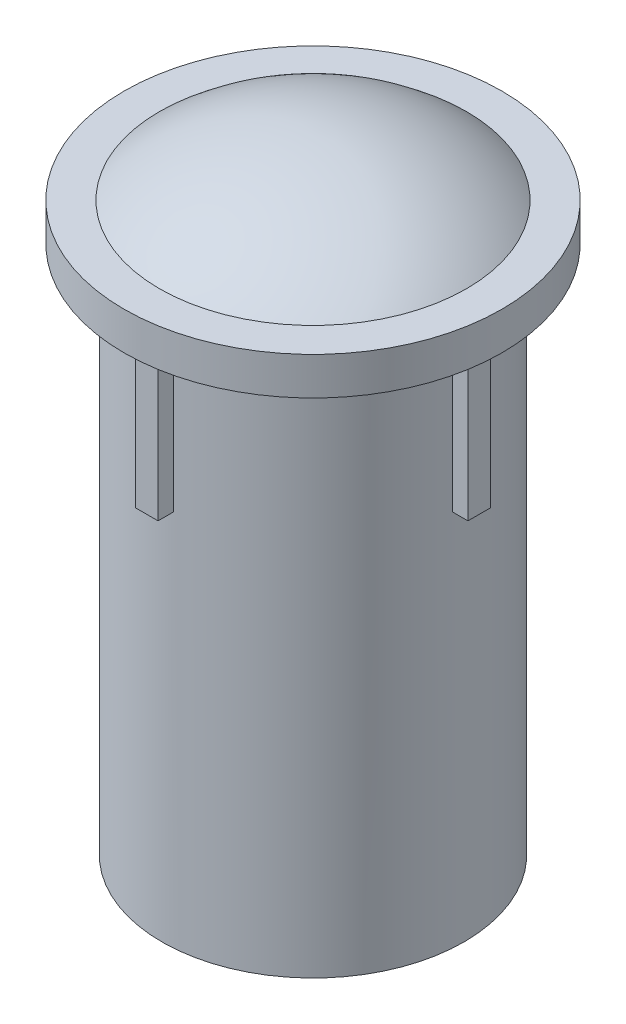
SolidWorks part; units mm, degrees
ref_plane "前视基准面" through (0, 0, 0) normal (0, 0, 1) x (1, 0, 0)
ref_plane "上视基准面" through (0, 0, 0) normal (0, 1, 0) x (1, 0, 0)
ref_plane "右视基准面" through (0, 0, 0) normal (1, 0, 0) x (0, 0, -1)
sketch "草图1" plane through (0, 0, 0) normal (0, 1, 0) x (1, 0, 0)
  circle A0 centre (0, 0) radius 2.5
  dimension "D1" = 5
extrude "凸台-拉伸1" add sketch "草图1" along normal blind 0.5
sketch "草图2" plane through (0, 0, 0) normal (0, 0, 1) x (1, 0, 0)
  line L0 (0, 3.6712) -> (0, -4.822) construction
  line L1 (-2.5, 0) -> (2.5, 0) construction
  line L2 (2.5, 0) -> (0, 0)
  line L3 (0, 0) -> (0, 1.25)
  arc A0 (0, 1.25) -> (2.5, 0) centre (0, -1.875) cw
  point P6 (0, -2.975)
  dimension "D1" = 1.25
revolve "旋转4" add sketch "草图2" angle 360 about L0
sketch "草图4" plane through (0, 0, 0) normal (0, -1, 0) x (1, 0, 0)
  circle A0 centre (0, 0) radius 2
  dimension "D1" = 4
extrude "凸台-拉伸2" add sketch "草图4" along normal blind 7
sketch "草图5" plane through (0, 0, 0) normal (0, -1, 0) x (1, 0, 0)
  line L0 (-3.0838, 0) -> (2.6625, 0) construction
  line L1 (-0.15, 2.2) -> (-0.15, 1.9074)
  line L2 (-2.2, -0.15) -> (-1.9074, -0.15)
  line L3 (-2.2, -0.15) -> (-2.2, 0.15)
  line L4 (-2.2, 0.15) -> (-1.9074, 0.15)
  line L5 (-1.9074, -0.15) -> (-1.9074, 0.15)
  line L6 (-0.15, 2.2) -> (0.15, 2.2)
  line L7 (0.15, 2.2) -> (0.15, 1.9074)
  line L8 (-0.15, 1.9074) -> (0.15, 1.9074)
  line L9 (2.2, 0.15) -> (1.9074, 0.15)
  line L10 (2.2, 0.15) -> (2.2, -0.15)
  line L11 (2.2, -0.15) -> (1.9074, -0.15)
  line L12 (1.9074, 0.15) -> (1.9074, -0.15)
  line L13 (0.15, -2.2) -> (0.15, -1.9074)
  line L14 (0.15, -2.2) -> (-0.15, -2.2)
  line L15 (-0.15, -2.2) -> (-0.15, -1.9074)
  line L16 (0.15, -1.9074) -> (-0.15, -1.9074)
  point P22 (0, 0)
  dimension "D1" = 0.3
  dimension "D2" = 2.2
  dimension "D3" = 4
extrude "凸台-拉伸3" add sketch "草图5" along normal blind 2
